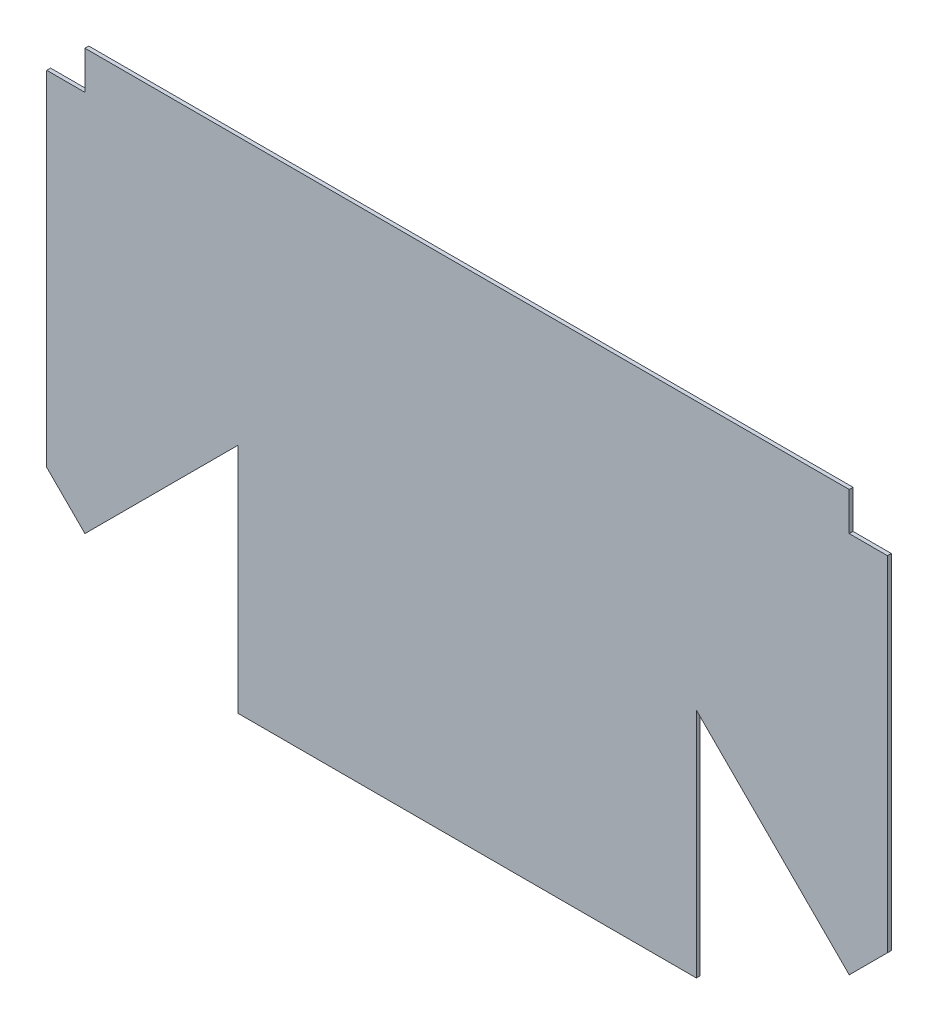
SolidWorks part; units mm, degrees
ref_plane "Front" through (0, 0, 0) normal (0, 0, 1) x (1, 0, 0)
ref_plane "Top" through (0, 0, 0) normal (0, 1, 0) x (1, 0, 0)
ref_plane "Right" through (0, 0, 0) normal (1, 0, 0) x (0, 0, -1)
sketch "Croquis1" plane through (0, 0, 0) normal (0, 0, 1) x (1, 0, 0)
  line L38 (0, 0) -> (-10, 0)
  line L40 (-10, 0) -> (-60, 0) construction
  line L41 (-60, 0) -> (-160, 0) construction
  line L44 (-10, 0) -> (-10, -100) construction
  line L46 (-60, 0) -> (-60, -50) construction
  line L48 (-10, -100) -> (-50, -60)
  line L51 (-110, 0) -> (-110, -120.7107) construction
  line L52 (0, 0) -> (0, -90)
  line L53 (0, -90) -> (-10, -100)
  line L54 (-160, 0) -> (-160, -50) construction
  line L55 (-210, 0) -> (-210, -100) construction
  line L56 (-220, -90) -> (-210, -100)
  line L57 (-220, 0) -> (-220, -90)
  line L59 (-210, -100) -> (-170, -60)
  line L60 (-210, 0) -> (-160, 0) construction
  line L61 (-220, 0) -> (-210, 0)
  line L62 (-50, -60) -> (-50, -120.7107)
  line L64 (-170, -60) -> (-170, -120.7107)
  line L65 (-10, 0) -> (-10, 10)
  line L66 (-10, 10) -> (-210, 10)
  line L67 (-210, 10) -> (-210, 0)
  line L68 (-170, -120.7107) -> (-50, -120.7107)
  circle A0 centre (-60, -50) radius 70.7107 construction
  circle A1 centre (-160, -50) radius 70.7107 construction
  point P19 (0, 0)
  dimension "D1" = 10
  dimension "D2" = 50
  dimension "D3" = 50
  dimension "D4" = 100
  dimension "D5" = 50
  dimension "D6" = 90
  dimension "D8" = 10
extrude "Saliente-Extruir1" add sketch "Croquis1" along normal blind 1
